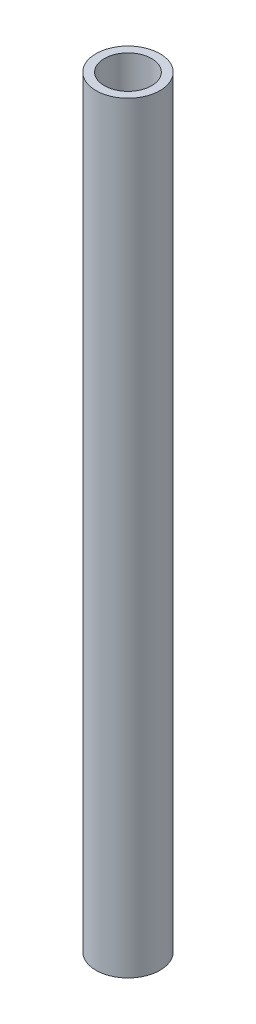
SolidWorks part; units mm, degrees
ref_plane "Front Plane" through (0, 0, 0) normal (0, 0, 1) x (1, 0, 0)
ref_plane "Top Plane" through (0, 0, 0) normal (0, 1, 0) x (1, 0, 0)
ref_plane "Right Plane" through (0, 0, 0) normal (1, 0, 0) x (0, 0, -1)
sketch "Sketch1" plane through (0, 0, 0) normal (0, 1, 0) x (1, 0, 0)
  circle A0 centre (0, 0) radius 7.874
  circle A1 centre (0, 0) radius 10.668
  dimension "D1" = 15.748
  dimension "D2" = 21.336
extrude "Boss-Extrude1" add sketch "Sketch1" along normal mid plane 254
